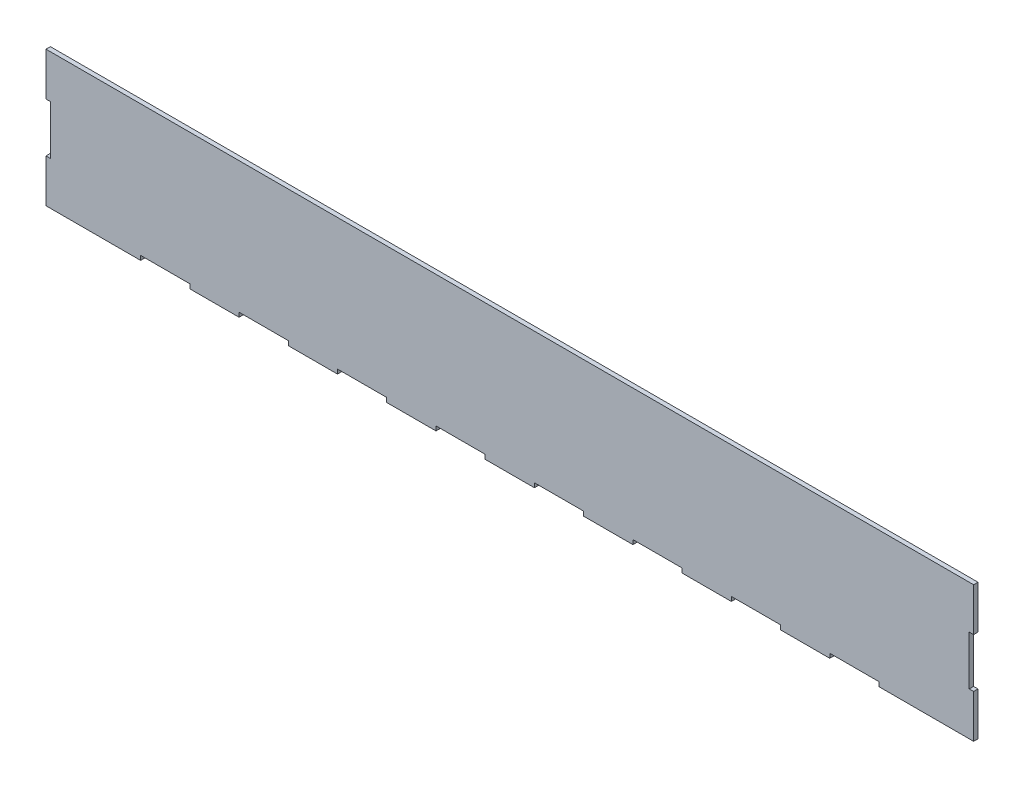
SolidWorks part; units mm, degrees
ref_plane "Front Plane" through (0, 0, 0) normal (0, 0, 1) x (1, 0, 0)
ref_plane "Top Plane" through (0, 0, 0) normal (0, 1, 0) x (1, 0, 0)
ref_plane "Right Plane" through (0, 0, 0) normal (1, 0, 0) x (0, 0, -1)
sketch "Model" plane through (0, 0, 0) normal (0, 0, 1) x (1, 0, 0)
  line L0 (0, 192) -> (0, 162.375)
  line L1 (0, 162.375) -> (3, 162.375)
  line L2 (3, 162.375) -> (3, 128.625)
  line L3 (3, 128.625) -> (0, 128.625)
  line L4 (0, 128.625) -> (0, 99)
  line L5 (0, 99) -> (64.875, 99)
  line L6 (64.875, 99) -> (64.875, 102)
  line L7 (64.875, 102) -> (98.625, 102)
  line L8 (98.625, 102) -> (98.625, 99)
  line L9 (98.625, 99) -> (132.375, 99)
  line L10 (132.375, 99) -> (132.375, 102)
  line L11 (132.375, 102) -> (166.125, 102)
  line L12 (166.125, 102) -> (166.125, 99)
  line L13 (166.125, 99) -> (199.875, 99)
  line L14 (199.875, 99) -> (199.875, 102)
  line L15 (199.875, 102) -> (233.625, 102)
  line L16 (233.625, 102) -> (233.625, 99)
  line L17 (233.625, 99) -> (267.375, 99)
  line L18 (267.375, 99) -> (267.375, 102)
  line L19 (267.375, 102) -> (301.125, 102)
  line L20 (301.125, 102) -> (301.125, 99)
  line L21 (301.125, 99) -> (334.875, 99)
  line L22 (334.875, 99) -> (334.875, 102)
  line L23 (334.875, 102) -> (368.625, 102)
  line L24 (368.625, 102) -> (368.625, 99)
  line L25 (368.625, 99) -> (402.375, 99)
  line L26 (402.375, 99) -> (402.375, 102)
  line L27 (402.375, 102) -> (436.125, 102)
  line L28 (436.125, 102) -> (436.125, 99)
  line L29 (436.125, 99) -> (469.875, 99)
  line L30 (469.875, 99) -> (469.875, 102)
  line L31 (469.875, 102) -> (503.625, 102)
  line L32 (503.625, 102) -> (503.625, 99)
  line L33 (503.625, 99) -> (537.375, 99)
  line L34 (537.375, 99) -> (537.375, 102)
  line L35 (537.375, 102) -> (571.125, 102)
  line L36 (571.125, 102) -> (571.125, 99)
  line L37 (571.125, 99) -> (604.875, 99)
  line L38 (604.875, 99) -> (636, 99)
  line L39 (636, 99) -> (636, 128.625)
  line L40 (636, 128.625) -> (633, 128.625)
  line L41 (633, 128.625) -> (633, 162.375)
  line L42 (633, 162.375) -> (636, 162.375)
  line L43 (636, 162.375) -> (636, 192)
  line L44 (636, 192) -> (0, 192)
extrude "Boss-Extrude1" add sketch "Model" along normal blind 3
